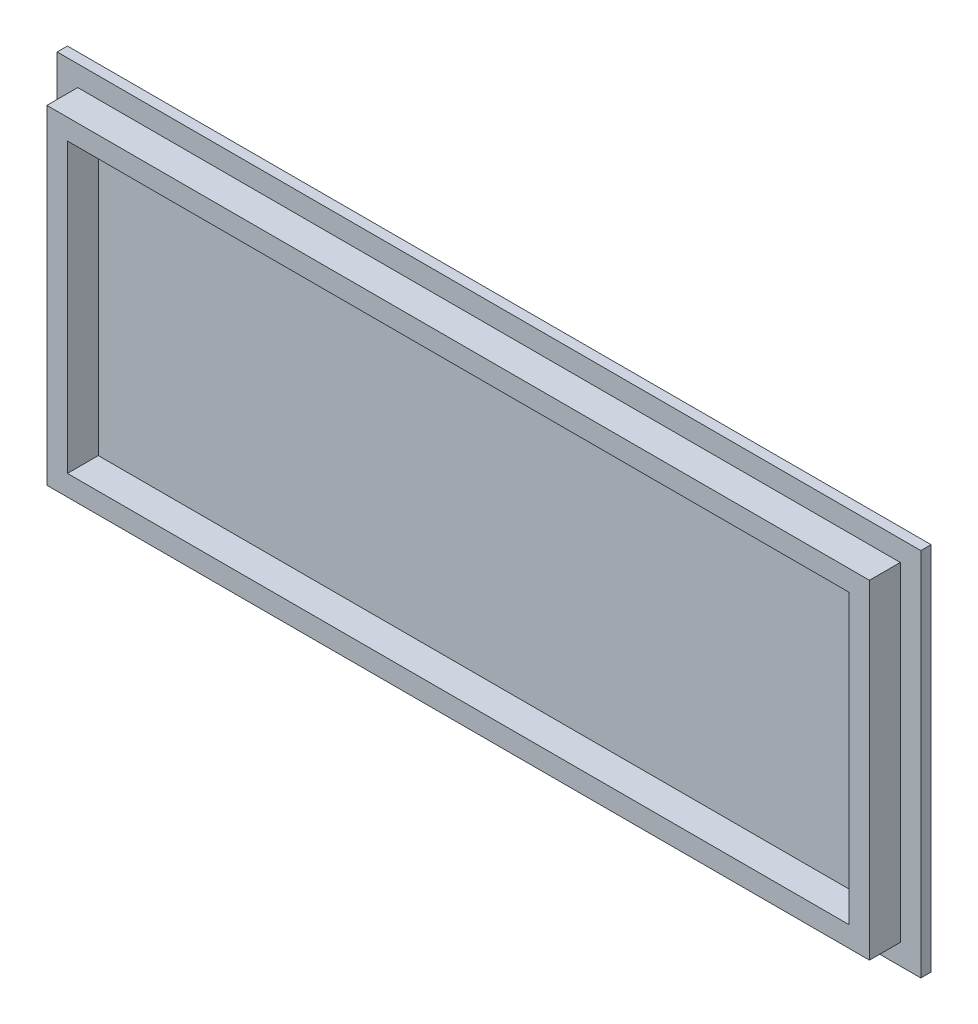
SolidWorks part; units mm, degrees
material "ABS"
ref_plane "Front Plane" through (0, 0, 0) normal (0, 0, 1) x (1, 0, 0)
ref_plane "Top Plane" through (0, 0, 0) normal (0, 1, 0) x (1, 0, 0)
ref_plane "Right Plane" through (0, 0, 0) normal (1, 0, 0) x (0, 0, -1)
sketch "Sketch1" plane through (0, 0, 0) normal (0, 0, 1) x (1, 0, 0)
  line L1 (0, 0) -> (84, 0)
  line L2 (0, 0) -> (0, 36)
  line L3 (0, 36) -> (84, 36)
  line L4 (84, 0) -> (84, 36)
  dimension "D1" = 84
  dimension "D2" = 36
extrude "Boss-Extrude1" add sketch "Sketch1" along normal blind 1
sketch "Sketch2" plane through (0, 0, 1) normal (0, 0, 1) x (1, 0, 0)
  line L0 (0, 0) -> (84, 36) construction
  line L1 (4, 32) -> (80, 32)
  line L2 (2, 2) -> (82, 2)
  line L3 (2, 2) -> (2, 34)
  line L4 (2, 34) -> (82, 34)
  line L5 (82, 2) -> (82, 34)
  line L6 (2, 2) -> (82, 34) construction
  line L7 (2, 34) -> (82, 2) construction
  line L8 (80, 4) -> (80, 32)
  line L9 (4, 4) -> (80, 4)
  line L10 (4, 4) -> (4, 32)
  line L11 (0, 0) -> (84, 0) construction
  line L12 (84, 0) -> (84, 36) construction
  point P4 (42, 18)
  dimension "D1" = 2
  dimension "D2" = 2
  dimension "D3" = 2
extrude "Boss-Extrude2" add sketch "Sketch2" along normal blind 3
equation "\"behindCoverLegth\"=84"
equation "\"D1@Sketch1\"=\"behindCoverLegth\""
